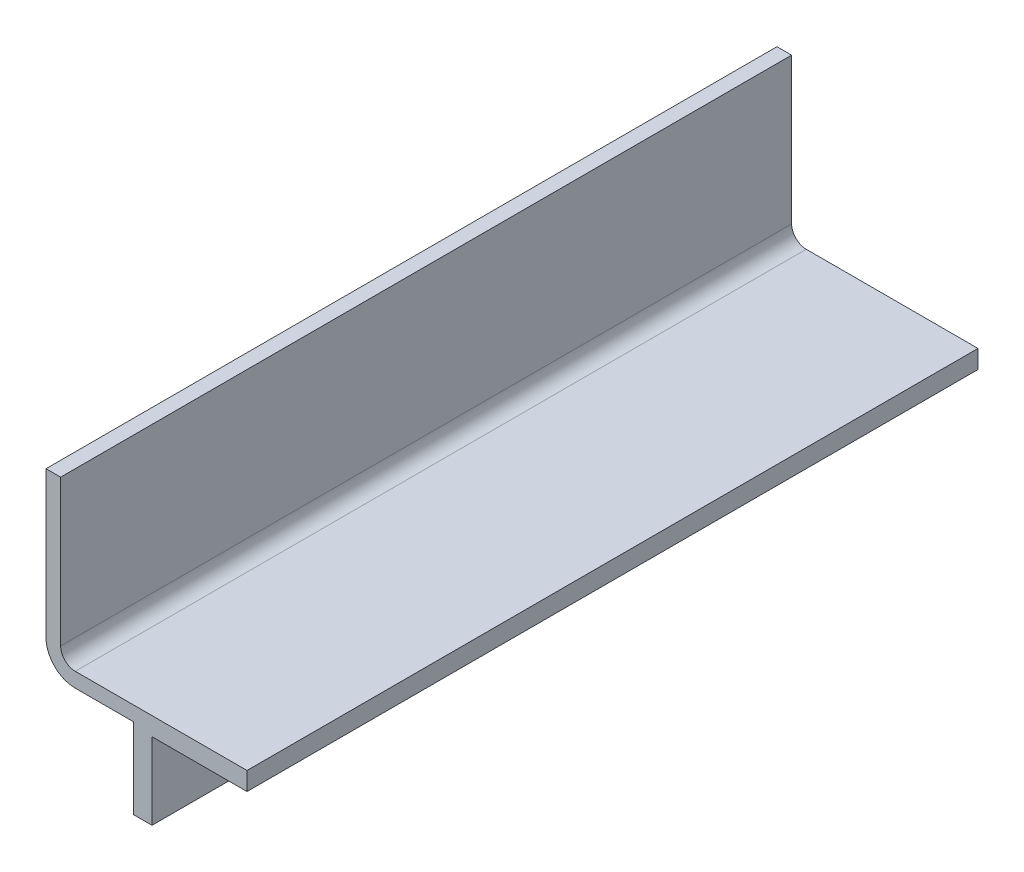
SolidWorks part; units mm, degrees
material "ABS generico"
ref_plane "Piano frontale" through (0, 0, 0) normal (0, 0, 1) x (1, 0, 0)
ref_plane "Piano superiore" through (0, 0, 0) normal (0, 1, 0) x (1, 0, 0)
ref_plane "Piano destro" through (0, 0, 0) normal (1, 0, 0) x (0, 0, -1)
sketch "Schizzo1" plane through (0, 0, 0) normal (0, 0, 1) x (1, 0, 0)
  line L0 (-2.5, 0) -> (0, 0)
  line L1 (0, 0) -> (0, 10.5)
  line L2 (0, 10.5) -> (13, 10.5)
  line L3 (13, 10.5) -> (13, 13)
  line L4 (13, 13) -> (-10.5, 13)
  line L5 (-12.5, 15) -> (-12.5, 35)
  line L6 (-12.5, 35) -> (-14.5, 35)
  line L7 (-14.5, 35) -> (-14.5, 15)
  line L8 (-10.5, 11) -> (-2.5, 11)
  line L9 (-2.5, 11) -> (-2.5, 0)
  arc A0 (-10.5, 11) -> (-14.5, 15) centre (-10.5, 15) cw
  arc A1 (-12.5, 15) -> (-10.5, 13) centre (-10.5, 15) ccw
  point P13 (-14.5, 11)
  dimension "D9" = 4
  dimension "D10" = 2
  dimension "D1" = 2.5
  dimension "D2" = 13
  dimension "D3" = 15.5
  dimension "D4" = 10.5
  dimension "D5" = 11
  dimension "D6" = 12
  dimension "D7" = 2
  dimension "D8" = 24
extrude "Estrusione-Estrusione1" add sketch "Schizzo1" along normal blind 100
sketch "Schizzo3" plane through (-2.5, 0, 0) normal (-1, 0, 0) x (0, 0, 1)
  line L0 (15, 4.5) -> (85, 4.5) construction
  line L2 (100, 0) -> (0, 0) construction
  line L3 (0, 11) -> (0, 0) construction
  line L4 (100, 11) -> (100, 0) construction
  point P0 (15, 4.5)
  point P2 (85, 4.5)
  dimension "D1" = 4.5
  dimension "D2" = 15
  dimension "D3" = 15
hole_wizard "Foro per Vite M4-1" positions "Schizzo3" profile "Schizzo5" hole size "M4" standard "ISO"
sketch "Schizzo5" plane through (-2.5, 4.5, 15) normal (0, 1, 0) x (0, 0, 1)
  line L0 (0, 0) -> (0, 31.3519)
  line L1 (0, 31.3519) -> (2.25, 30)
  line L2 (2.25, 30) -> (2.25, 0)
  line L5 (2.25, 0) -> (0, 0)
  line L10 (0, 31.3519) -> (-2.25, 30) construction
  line L11 (0, -6.35) -> (0, 107.95) construction
  dimension "Hole Dia." = 4.5
  dimension "Hole Depth" = 30
  dimension "Drill Angle" = 118
